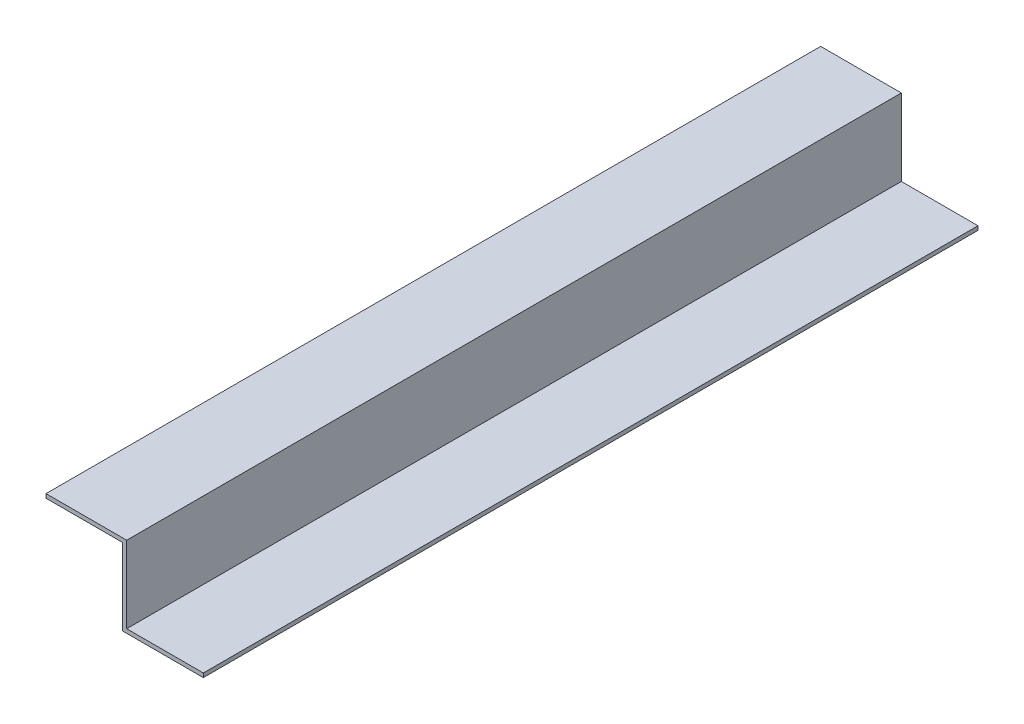
SolidWorks part; units mm, degrees
ref_plane "Front Plane" through (0, 0, 0) normal (0, 0, 1) x (1, 0, 0)
ref_plane "Top Plane" through (0, 0, 0) normal (0, 1, 0) x (1, 0, 0)
ref_plane "Right Plane" through (0, 0, 0) normal (1, 0, 0) x (0, 0, -1)
sketch "Sketch1" plane through (0, 0, 0) normal (0, 0, 1) x (1, 0, 0)
  line L0 (0, -15.0813) -> (0, 15.0813) construction
  line L1 (0, 15.0813) -> (-30.9563, 15.0813) construction
  line L2 (0, -15.0813) -> (30.9563, -15.0812) construction
  line L3 (0.7937, -14.2875) -> (30.9563, -14.2875) construction
  line L4 (0.7937, -14.2875) -> (0.7937, 15.875) construction
  line L5 (0.7937, 15.875) -> (-30.9563, 15.875) construction
  line L6 (-0.7937, -15.875) -> (30.9563, -15.875) construction
  line L7 (-0.7937, -15.875) -> (-0.7937, 14.2875) construction
  line L8 (-0.7937, 14.2875) -> (-30.9563, 14.2875) construction
  line L9 (-30.9563, 15.875) -> (-30.9563, 14.2875) construction
  line L10 (30.9563, -14.2875) -> (30.9563, -15.875) construction
  point P4 (0, 0)
  dimension "Leg Width" = 31.75
  dimension "Outside Height" = 31.75
  dimension "Wall Thickness" = 1.5875
sketch "Sketch2" plane through (0, 0, 0) normal (1, 0, 0) x (0, 0, -1)
  line L0 (152.4, 0) -> (-152.4, 0) construction
  line L1 (0, 0) -> (0, 15.875) construction
  line L2 (-152.4, 0) -> (-152.4, 15.875) construction
  line L3 (152.4, 0) -> (152.4, 15.875) construction
  point P0 (-114.3, 0)
  point P3 (114.3, 0)
  point P4 (0, 0)
  dimension "D1" = 228.6
  dimension "Length" = 304.8
sketch "Sketch3" plane through (0, 0, 0) normal (0, 0, 1) x (1, 0, 0)
  line L0 (30.9563, -14.2875) -> (30.9563, -15.875) construction
  line L1 (0.7937, -14.2875) -> (30.9563, -14.2875) construction
  line L2 (-0.7937, -15.875) -> (30.9563, -15.875) construction
  line L3 (-0.7937, -15.875) -> (-0.7937, 14.2875) construction
  line L4 (0.7937, -14.2875) -> (0.7937, 15.875) construction
  line L5 (0.7937, 15.875) -> (-30.9563, 15.875) construction
  line L6 (-30.9563, 15.875) -> (-30.9563, 14.2875) construction
  line L7 (-0.7937, 14.2875) -> (-30.9563, 14.2875) construction
  line L8 (30.9563, -14.2875) -> (30.9563, -15.875)
  line L9 (0.7937, -14.2875) -> (30.9563, -14.2875)
  line L10 (-0.7937, -15.875) -> (30.9563, -15.875)
  line L11 (-0.7937, -15.875) -> (-0.7937, 14.2875)
  line L12 (0.7937, -14.2875) -> (0.7937, 15.875)
  line L13 (0.7937, 15.875) -> (-30.9563, 15.875)
  line L14 (-30.9563, 15.875) -> (-30.9563, 14.2875)
  line L15 (-0.7937, 14.2875) -> (-30.9563, 14.2875)
extrude "Boss-Extrude1" add sketch "Sketch3" along normal up to vertex (152.4 mm away) and the other way up to vertex (152.4 mm away) up to point (0, 0, 152.4) other way up to point (0, 0, -152.4)
sketch "Sketch6" plane through (0, -14.2875, 0) normal (0, 1, 0) x (1, 0, 0)
  line L0 (0.7937, -152.4) -> (0.7937, 152.4) construction
  line L2 (12.5031, -133.35) -> (12.5032, -152.4) construction
  line L3 (30.9563, -152.4) -> (0.7937, -152.4) construction
  line L4 (12.5031, -133.35) -> (12.5031, -124.46) construction
  line L5 (12.5031, -124.46) -> (12.5031, -48.26) construction
  line L6 (12.5031, -48.26) -> (12.5031, 27.94) construction
  circle A0 centre (12.5031, -124.46) radius 1.5875
  circle A1 centre (12.5031, 27.94) radius 1.5875
  circle A2 centre (12.5031, -48.26) radius 1.5875
  dimension "D1" = 11.7094
  dimension "D6" = 3.175
  dimension "D2" = 19.05
  dimension "D3" = 8.89
  dimension "D4" = 76.2
  dimension "D5" = 76.2
equation "\"D1@Sketch2\"=\"Length@Sketch2\"*0.75"
